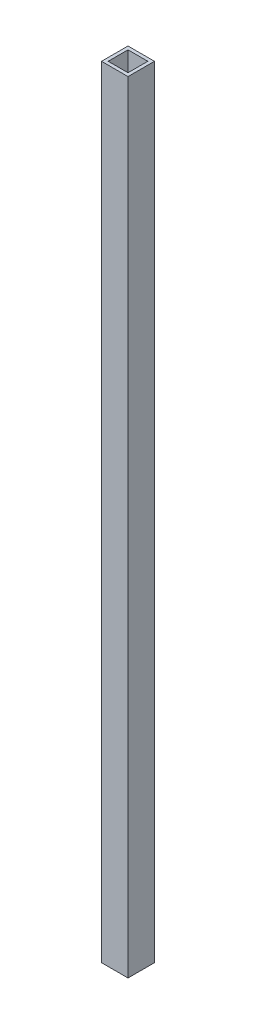
SolidWorks part; units mm, degrees
ref_plane "Front Plane" through (0, 0, 0) normal (0, 0, 1) x (1, 0, 0)
ref_plane "Top Plane" through (0, 0, 0) normal (0, 1, 0) x (1, 0, 0)
ref_plane "Right Plane" through (0, 0, 0) normal (1, 0, 0) x (0, 0, -1)
sketch "Sketch1" plane through (0, 0, 0) normal (0, 1, 0) x (1, 0, 0)
  line L1 (-12.7, -12.7) -> (12.7, -12.7)
  line L2 (-12.7, -12.7) -> (-12.7, 12.7)
  line L3 (-12.7, 12.7) -> (12.7, 12.7)
  line L4 (12.7, -12.7) -> (12.7, 12.7)
  line L5 (-12.7, -12.7) -> (12.7, 12.7) construction
  line L6 (-12.7, 12.7) -> (12.7, -12.7) construction
  line L7 (-9.525, 9.525) -> (9.525, 9.525)
  line L8 (-9.525, 9.525) -> (-9.525, -9.525)
  line L9 (-9.525, -9.525) -> (9.525, -9.525)
  line L10 (9.525, 9.525) -> (9.525, -9.525)
  line L11 (-9.525, 9.525) -> (9.525, -9.525) construction
  line L12 (-9.525, -9.525) -> (9.525, 9.525) construction
  point P0 (0, 0)
  point P6 (0, 0)
  dimension "D1" = 25.4
  dimension "D2" = 25.4
  dimension "D3" = 19.05
extrude "Boss-Extrude1" add sketch "Sketch1" along normal blind 749.3
